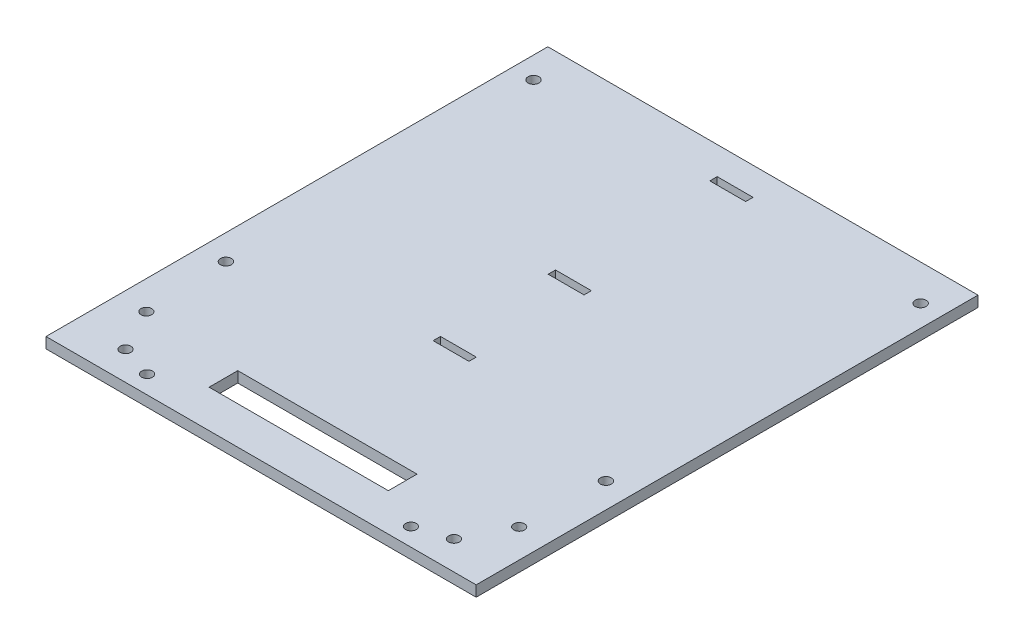
SolidWorks part; units mm, degrees
ref_plane "Front Plane" through (0, 0, 0) normal (0, 0, 1) x (1, 0, 0)
ref_plane "Top Plane" through (0, 0, 0) normal (0, 1, 0) x (1, 0, 0)
ref_plane "Right Plane" through (0, 0, 0) normal (1, 0, 0) x (0, 0, -1)
sketch "Sketch1" plane through (0, 0, 0) normal (0, 1, 0) x (1, 0, 0)
  line L1 (60, -70) -> (-60, -70)
  line L2 (60, -70) -> (60, 70)
  line L3 (60, 70) -> (-60, 70)
  line L4 (-60, -70) -> (-60, 70)
  line L5 (60, -70) -> (-60, 70) construction
  line L6 (60, 70) -> (-60, -70) construction
  point P0 (0, 0)
  dimension "D1" = 140
  dimension "D2" = 120
extrude "Boss-Extrude1" add sketch "Sketch1" along normal blind 3
sketch "Sketch2" plane through (0, 3, 0) normal (0, 1, 0) x (1, 0, 0)
  line L0 (0, 0) -> (0, 70) construction
  line L1 (60, 70) -> (-60, 70) construction
  line L2 (-60, 70) -> (-60, -70) construction
  circle A0 centre (-53, -26.81) radius 1.525
  circle A1 centre (-54, 60) radius 1.525
  circle A2 centre (53, -26.81) radius 1.525
  circle A3 centre (54, 60) radius 1.525
  dimension "D1" = 10
  dimension "D2" = 3.05
  dimension "D3" = 6
  dimension "D4" = 3.05
  dimension "D5" = 7
  dimension "D6" = 86.81
extrude "Cut-Extrude1" cut sketch "Sketch2" against normal through all
sketch "Sketch3" plane through (0, 3, 0) normal (0, 1, 0) x (1, 0, 0)
  line L0 (-5, 17.14) -> (5, 17.14)
  line L1 (-5, -14.96) -> (5, -14.96)
  line L2 (-5, -14.96) -> (-5, -17.01)
  line L3 (-5, -17.01) -> (5, -17.01)
  line L4 (5, -14.96) -> (5, -17.01)
  line L5 (-5, -14.96) -> (5, -17.01) construction
  line L6 (-5, -17.01) -> (5, -14.96) construction
  line L7 (-5, 17.14) -> (-5, 15.09)
  line L8 (-5, 15.09) -> (5, 15.09)
  line L9 (5, 17.14) -> (5, 15.09)
  line L11 (-5, 62.24) -> (5, 62.24)
  line L12 (-5, 62.24) -> (-5, 60.19)
  line L13 (-5, 60.19) -> (5, 60.19)
  line L14 (-5, 49.24) -> (5, 49.24) [skipped]
  line L15 (-5, 49.24) -> (-5, 47.19) [skipped]
  line L16 (-5, 47.19) -> (5, 47.19) [skipped]
  line L17 (5, 49.24) -> (5, 47.19) [skipped]
  line L18 (5, 62.24) -> (5, 60.19)
  line L19 (-5, 62.24) -> (5, 60.19) construction
  line L20 (-5, 60.19) -> (5, 62.24) construction
  circle A0 centre (-53, -26.81) radius 1.525 construction
  point P0 (0, -15.985)
  point P8 (0, 61.215)
  dimension "D2" = 9.8
  dimension "D1" = 2.05
  dimension "D3" = 10
  dimension "D4" = 0
  dimension "D6" = 2.05
  dimension "D7" = 10
  dimension "D8" = 0
  dimension "D9" = 43.05
  dimension "D10" = 30.05
  dimension "D5" = 3
extrude "Cut-Extrude2" cut sketch "Sketch3" against normal through all
sketch "Sketch4" plane through (0, 3, 0) normal (0, 1, 0) x (1, 0, 0)
  line L0 (-60, -70) -> (60, -70) construction
  line L1 (-60, 70) -> (-60, -70) construction
  line L2 (0, 0) -> (0, -70) construction
  circle A1 centre (-52, -50) radius 1.5
  circle A2 centre (-45.8153, -62) radius 1.5
  circle A3 centre (45.8153, -62) radius 1.5
  circle A4 centre (52, -50) radius 1.5
  dimension "D1" = 3
  dimension "D2" = 3
  dimension "D4" = 8
  dimension "D5" = 13.5
  dimension "D6" = 8
  dimension "D3" = 20
extrude "Cut-Extrude3" cut sketch "Sketch4" against normal blind 3
sketch "Sketch5" plane through (0, 3, 0) normal (0, 1, 0) x (1, 0, 0)
  line L0 (0, 0) -> (0, -70) construction
  line L2 (25, -59.5) -> (-25, -59.5)
  line L3 (25, -59.5) -> (25, -51.5)
  line L4 (25, -51.5) -> (-25, -51.5)
  line L5 (-25, -59.5) -> (-25, -51.5)
  line L6 (25, -59.5) -> (-25, -51.5) construction
  line L7 (-60, -70) -> (60, -70) construction
  line L8 (25, -51.5) -> (-25, -59.5) construction
  circle A0 centre (-36.8, -65) radius 1.5
  circle A1 centre (36.8, -65) radius 1.5
  point P0 (0, -55.5)
  dimension "D3" = 3
  dimension "D4" = 5.5
  dimension "D5" = 5
  dimension "D1" = 8
  dimension "D2" = 50
  dimension "D6" = 36.8
extrude "Cut-Extrude4" cut sketch "Sketch5" against normal blind 3
